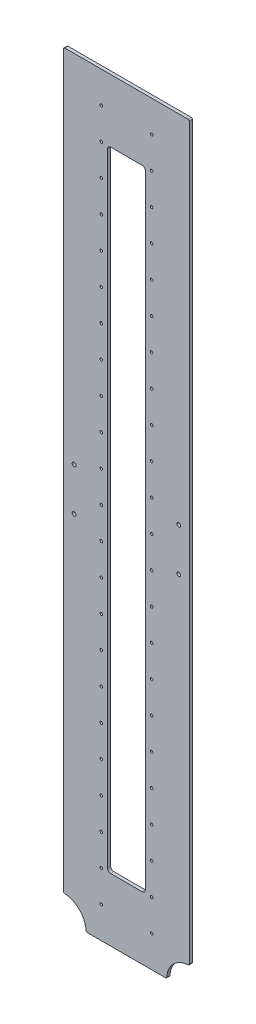
SolidWorks part; units mm, degrees
material "Acrylic (Medium-high impact)"
ref_plane "Front Plane" through (0, 0, 0) normal (0, 0, 1) x (1, 0, 0)
ref_plane "Top Plane" through (0, 0, 0) normal (0, 1, 0) x (1, 0, 0)
ref_plane "Right Plane" through (0, 0, 0) normal (1, 0, 0) x (0, 0, -1)
sketch "Sketch1" plane through (0, 0, 0) normal (0, 0, 1) x (1, 0, 0)
  line L1 (-100, -600) -> (100, -600)
  line L2 (-100, -600) -> (-100, 600)
  line L3 (-100, 600) -> (100, 600)
  line L4 (100, -600) -> (100, 600)
  line L5 (-100, -600) -> (100, 600) construction
  line L6 (-100, 600) -> (100, -600) construction
  point P0 (0, 0)
  dimension "D1" = 1200
  dimension "D2" = 200
extrude "Boss-Extrude1" add sketch "Sketch1" along normal blind 5
sketch "Sketch3" plane through (0, 0, 5) normal (0, 0, 1) x (1, 0, 0)
  line L0 (101.9888, -564.1972) -> (100, -564.1972) construction
  line L1 (-100, -600) -> (-100, -564.1972)
  line L2 (100, -600) -> (100, 600) construction
  line L3 (-64.1972, -600) -> (-100, -600)
  line L4 (-100, -600) -> (100, -600) construction
  line L6 (64.1972, -600) -> (100, -600)
  line L7 (100, -600) -> (100, -564.1972)
  line L8 (0, -600) -> (0, 597.3099) construction
  line L9 (-250, 597.3099) -> (250, 597.3099) construction
  arc A0 (100, -564.1972) -> (64.1972, -600) centre (100, -600) ccw
  arc A1 (-100, -564.1972) -> (-64.1972, -600) centre (-100, -600) cw
extrude "Cut-Extrude1" cut sketch "Sketch3" against normal through all
sketch "Sketch5" plane through (0, 0, 5) normal (0, 0, 1) x (1, 0, 0)
  line L1 (-30, -500) -> (30, -500)
  line L2 (-30, -500) -> (-30, 500)
  line L3 (-30, 500) -> (30, 500)
  line L4 (30, -500) -> (30, 500)
  line L5 (-30, -500) -> (30, 500) construction
  line L6 (-30, 500) -> (30, -500) construction
  point P0 (0, 0)
  dimension "D1" = 60
  dimension "D2" = 1000
extrude "Cut-Extrude3" cut sketch "Sketch5" against normal through all
fillet "Fillet2" radius 5 4 edges at (-30, -500, 2.5) (30, -500, 2.5) (30, 500, 2.5) (-30, 500, 2.5)
sketch "Sketch6" plane through (0, 0, 5) normal (0, 0, 1) x (1, 0, 0)
  line L0 (0, 0) -> (0, 600) construction
  line L1 (100, 600) -> (-100, 600) construction
  circle A0 centre (83.1932, -34) radius 3
  circle A1 centre (83.1932, 34) radius 3
  circle A2 centre (-83.1932, 34) radius 3
  circle A3 centre (-83.1932, -34) radius 3
  dimension "D1" = 6
extrude "Cut-Extrude4" cut sketch "Sketch6" against normal through all
fillet "Fillet3" radius 2 6 edges at (100, -564.1972, 2.5) (-100, 600, 2.5) (-64.1972, -600, 2.5) (64.1972, -600, 2.5) (-100, -564.1972, 2.5) (100, 600, 2.5)
sketch "Sketch9" plane through (0, 0, 5) normal (0, 0, 1) x (1, 0, 0)
  line L0 (-40, 600) -> (-40, -600) construction
  line L1 (98, 600) -> (-98, 600) construction
  line L2 (-62.2501, -600) -> (62.2501, -600) construction
  line L3 (-30, 495) -> (-30, -495) construction
  circle A0 centre (-40, 550) radius 2.1
  circle A1 centre (-40, 500) radius 2.1
  circle A2 centre (-40, 450) radius 2.1
  circle A3 centre (-40, 400) radius 2.1
  circle A4 centre (-40, 350) radius 2.1
  circle A5 centre (-40, 300) radius 2.1
  circle A6 centre (-40, 250) radius 2.1
  circle A7 centre (-40, 200) radius 2.1
  circle A8 centre (-40, 150) radius 2.1
  circle A9 centre (-40, 100) radius 2.1
  circle A10 centre (-40, 50) radius 2.1
  circle A11 centre (-40, 0) radius 2.1
  circle A12 centre (-40, -50) radius 2.1
  circle A13 centre (-40, -100) radius 2.1
  circle A14 centre (-40, -150) radius 2.1
  circle A15 centre (-40, -200) radius 2.1
  circle A16 centre (-40, -250) radius 2.1
  circle A17 centre (-40, -300) radius 2.1
  circle A18 centre (-40, -350) radius 2.1
  circle A19 centre (-40, -400) radius 2.1
  circle A20 centre (-40, -450) radius 2.1
  circle A21 centre (-40, -500) radius 2.1
  circle A22 centre (-40, -550) radius 2.1
  dimension "D2" = 50
  dimension "D3" = 4.2
  dimension "D5" = 50
  dimension "D1" = 10
  dimension "D4" = 23
extrude "Cut-Extrude5" cut sketch "Sketch9" against normal through all
mirror "Mirror1" about plane through (0, 0, 0) normal (1, 0, 0) of "Cut-Extrude5"
